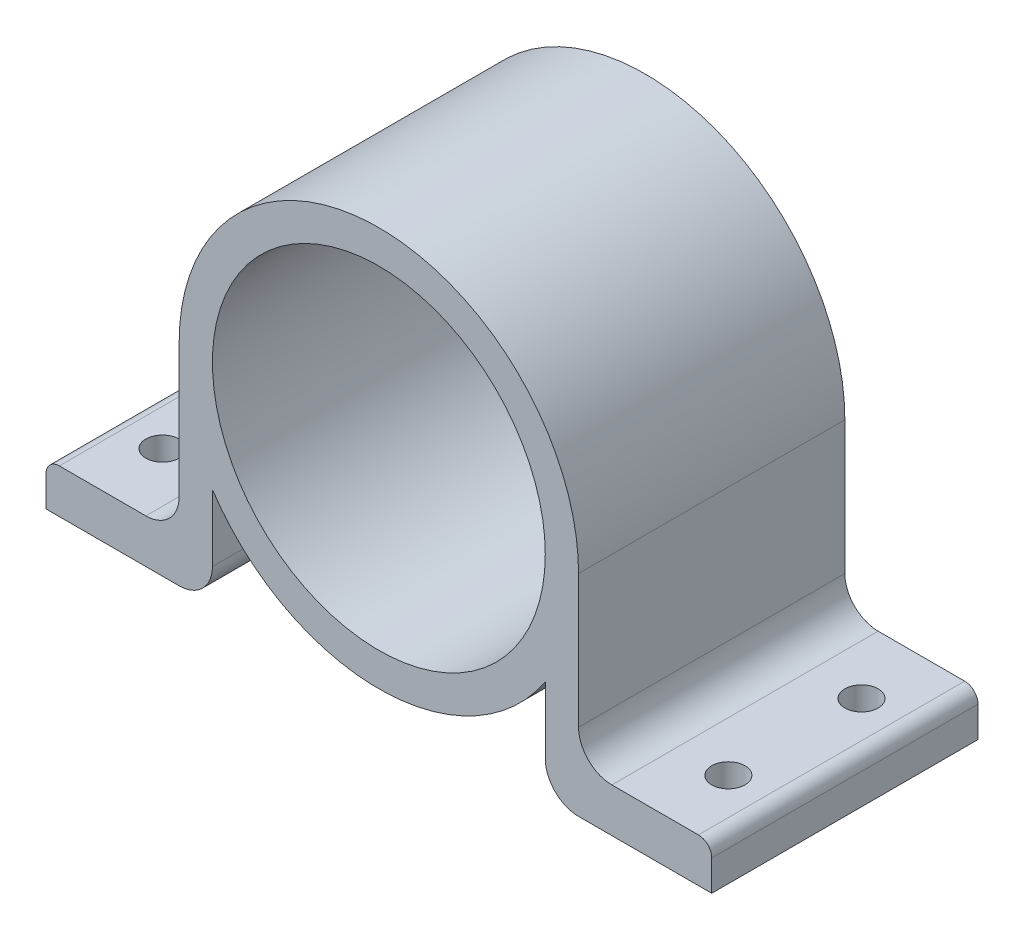
SolidWorks part; units mm, degrees
material "ABS"
ref_plane "Front Plane" through (0, 0, 0) normal (0, 0, 1) x (1, 0, 0)
ref_plane "Top Plane" through (0, 0, 0) normal (0, 1, 0) x (1, 0, 0)
ref_plane "Right Plane" through (0, 0, 0) normal (1, 0, 0) x (0, 0, -1)
sketch "Sketch1" plane through (0, 0, 0) normal (0, 0, 1) x (1, 0, 0)
  line L0 (0, -15.2958) -> (0, 29.6472) construction
  line L5 (-15, 19.0262) -> (15, 19.0262) construction
  line L6 (-25, 6.5262) -> (-15, 6.5262)
  line L8 (-25, 6.5262) -> (-25, 3.2262)
  line L10 (25, 6.5262) -> (25, 3.2262)
  line L11 (-7.9225, 4.0262) -> (8.1157, 4.0262) construction
  line L13 (-15, 6.5262) -> (-15, 19.0262)
  line L14 (15, 19.0262) -> (15, 6.5262)
  line L15 (15, 6.5262) -> (25, 6.5262)
  line L16 (-8.7492, 6.5262) -> (10.8103, 6.5262) construction
  line L17 (-25, 6.5262) -> (-25, -0.1738)
  line L19 (25, -0.1738) -> (25, 6.5262)
  line L20 (0, 36.5616) -> (0, 29.6472) construction
  line L26 (-12.5, 10.7346) -> (-12.5, 3.2262)
  line L27 (25, 3.2262) -> (12.5, 3.2262)
  line L32 (12.5, 10.7346) -> (12.5, 3.2262)
  line L35 (-25, 3.2262) -> (-12.5, 3.2262)
  circle A1 centre (0, 19.0262) radius 12.5
  arc A2 (15, 19.0262) -> (-15, 19.0262) centre (0, 19.0262) ccw
  arc A3 (-12.5, 10.7346) -> (12.5, 10.7346) centre (0, 19.0262) ccw
  point P0 (0, 0)
  point P6 (0, 0)
  point P9 (0, 32.4124)
  dimension "D4" = 3.3
  dimension "D3" = 25
  dimension "D5" = 25
  dimension "D1" = 3.3
  dimension "D2" = 25
extrude "Boss-Extrude1" add sketch "Sketch1" along normal blind 20
fillet "Fillet1" radius 2.5 2 edges at (-15, 6.5262, 10) (15, 6.5262, 10)
sketch "Sketch2" plane through (0, 6.5262, 0) normal (0, 1, 0) x (1, 0, 0)
  line L0 (-21.25, 0) -> (-21.25, -20) construction
  line L1 (-25, 0) -> (-17.5, 0) construction
  line L2 (-25, -20) -> (-17.5, -20) construction
  line L3 (21.25, 0) -> (21.25, -20) construction
  line L4 (17.5, 0) -> (25, 0) construction
  line L5 (17.5, -20) -> (25, -20) construction
  line L6 (-25, -5) -> (25, -5) construction
  line L7 (-25, -20) -> (-25, 0) construction
  line L8 (25, -20) -> (25, 0) construction
  line L9 (-25, -15) -> (25, -15) construction
  circle A0 centre (-21.25, -5) radius 1.25
  circle A1 centre (-21.25, -15) radius 1.25
  circle A2 centre (21.25, -5) radius 1.25
  circle A3 centre (21.25, -15) radius 1.25
  dimension "D3" = 2.5
  dimension "D4" = 2.5
  dimension "D5" = 2.5
  dimension "D6" = 2.5
  dimension "D1" = 5
  dimension "D2" = 5
extrude "Cut-Extrude1" cut sketch "Sketch2" against normal up to next
fillet "Fillet3" radius 1 2 edges at (-25, 6.5262, 10) (25, 6.5262, 10)
fillet "Fillet4" radius 2.5 2 edges at (12.5, 3.2262, 10) (-12.5, 3.2262, 10)
